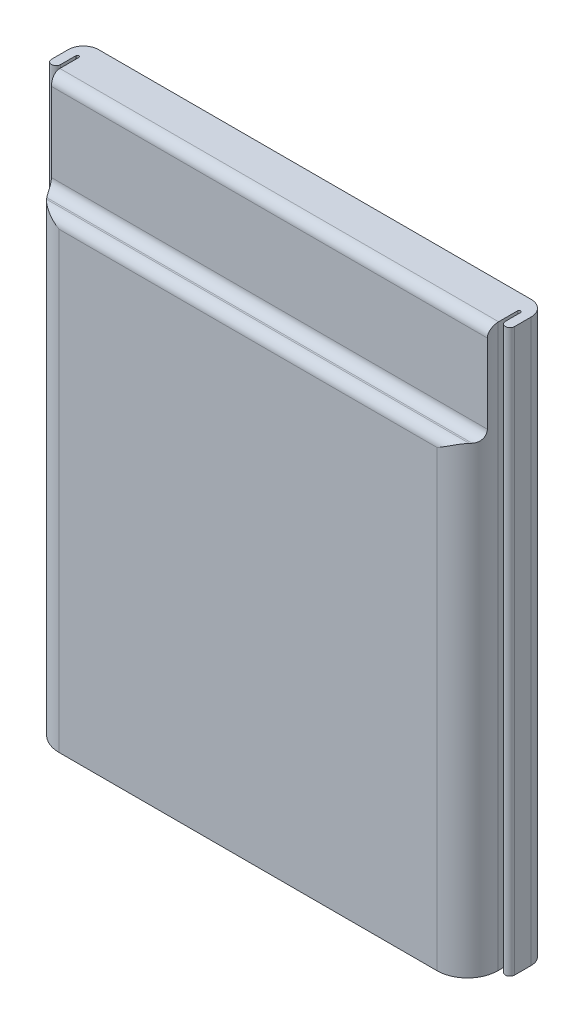
SolidWorks part; units mm, degrees
ref_plane "Front" through (0, 0, 0) normal (0, 0, 1) x (1, 0, 0)
ref_plane "Top" through (0, 0, 0) normal (0, 1, 0) x (1, 0, 0)
ref_plane "Right" through (0, 0, 0) normal (1, 0, 0) x (0, 0, -1)
sketch "Эскиз1" plane through (0, 0, 0) normal (0, 1, 0) x (1, 0, 0)
  line L0 (-14.25, 0) -> (14.25, 0)
  line L1 (-12.45, -4.4) -> (12.45, -4.4)
  line L2 (-15.25, -1) -> (-15.25, -2.1)
  line L3 (15.25, -1) -> (15.25, -2.1)
  line L4 (-14.45, -2.4) -> (-14.45, -1.1)
  line L5 (14.45, -1.1) -> (14.45, -2.4)
  line L6 (14.65, -2.1) -> (14.65, -1.1)
  line L7 (-14.65, -2.1) -> (-14.65, -1.1)
  arc A0 (-14.25, 0) -> (-15.25, -1) centre (-14.25, -1) ccw
  arc A1 (14.25, 0) -> (15.25, -1) centre (14.25, -1) cw
  arc A2 (-14.45, -2.4) -> (-12.45, -4.4) centre (-12.45, -2.4) ccw
  arc A3 (14.45, -2.4) -> (12.45, -4.4) centre (12.45, -2.4) cw
  arc A4 (15.25, -2.1) -> (14.65, -2.1) centre (14.95, -2.1) cw
  arc A5 (14.45, -1.1) -> (14.65, -1.1) centre (14.55, -1.1) cw
  arc A6 (-15.25, -2.1) -> (-14.65, -2.1) centre (-14.95, -2.1) ccw
  arc A7 (-14.45, -1.1) -> (-14.65, -1.1) centre (-14.55, -1.1) ccw
  point P20 (14.55, -1)
  point P21 (14.95, -2.4)
  point P27 (-14.55, -1)
  point P28 (-14.95, -2.4)
  dimension "D1" = 30.5
  dimension "D3" = 2
  dimension "D4" = 1
  dimension "D5" = 0.3
  dimension "D6" = 0.1
  dimension "D2" = 4.4
extrude "Бобышка-Вытянуть1" add sketch "Эскиз1" along normal mid plane 37
sketch "Эскиз2" plane through (0, 0, 0) normal (1, 0, 0) x (0, 0, -1)
  line L0 (-3, 17.85) -> (-3, 12.65)
  line L1 (-3.65, 12) -> (-3.75, 12)
  line L2 (-4.4, 18.5) -> (-4.4, 11.35)
  line L3 (-4.4, 18.5) -> (-4.4, -18.5) construction
  line L6 (-4.4, 18.5) -> (-2.35, 18.5)
  line L7 (0, 18.5) -> (-1, 18.5) construction
  arc A0 (-3, 12.65) -> (-3.65, 12) centre (-3.65, 12.65) cw
  arc A1 (-3.75, 12) -> (-4.4, 11.35) centre (-3.75, 11.35) ccw
  arc A2 (-2.35, 18.5) -> (-3, 17.85) centre (-2.35, 17.85) ccw
  dimension "D1" = 0.65
  dimension "D2" = 3
  dimension "D3" = 6.5
extrude "Вырез-Вытянуть1" cut sketch "Эскиз2" against normal up to next and the other way up to next
